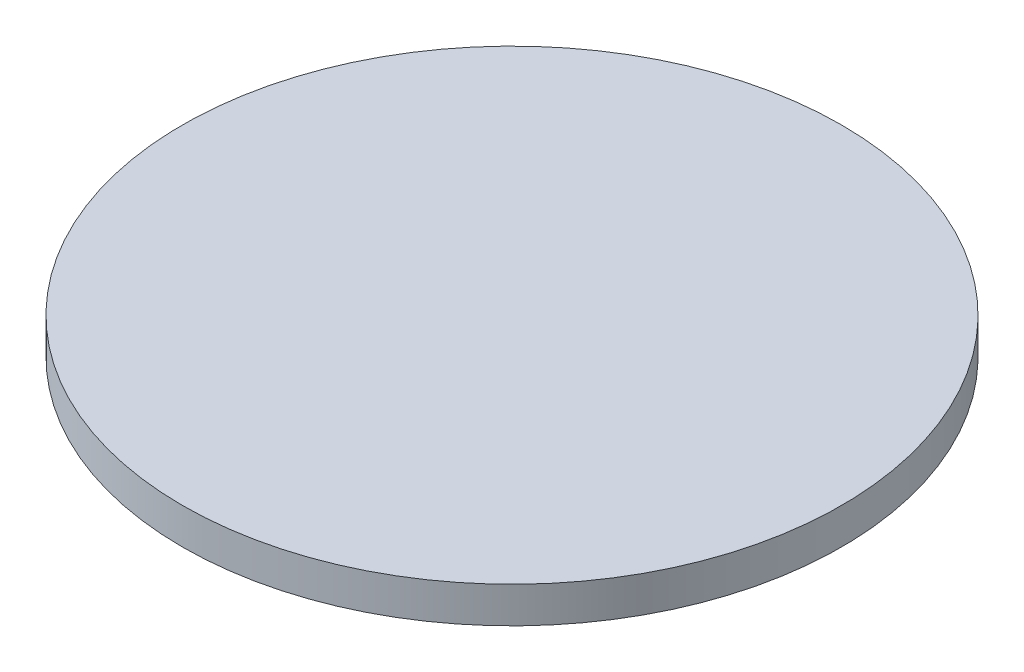
SolidWorks part; units mm, degrees
ref_plane "前视" through (0, 0, 0) normal (0, 0, 1) x (1, 0, 0)
ref_plane "上视" through (0, 0, 0) normal (0, 1, 0) x (1, 0, 0)
ref_plane "右视" through (0, 0, 0) normal (1, 0, 0) x (0, 0, -1)
sketch "草图1" plane through (0, 0, 0) normal (0, 1, 0) x (1, 0, 0)
  circle A0 centre (0, 0) radius 64
  dimension "D1" = 128
extrude "凸台-拉伸1" add sketch "草图1" along normal blind 7
